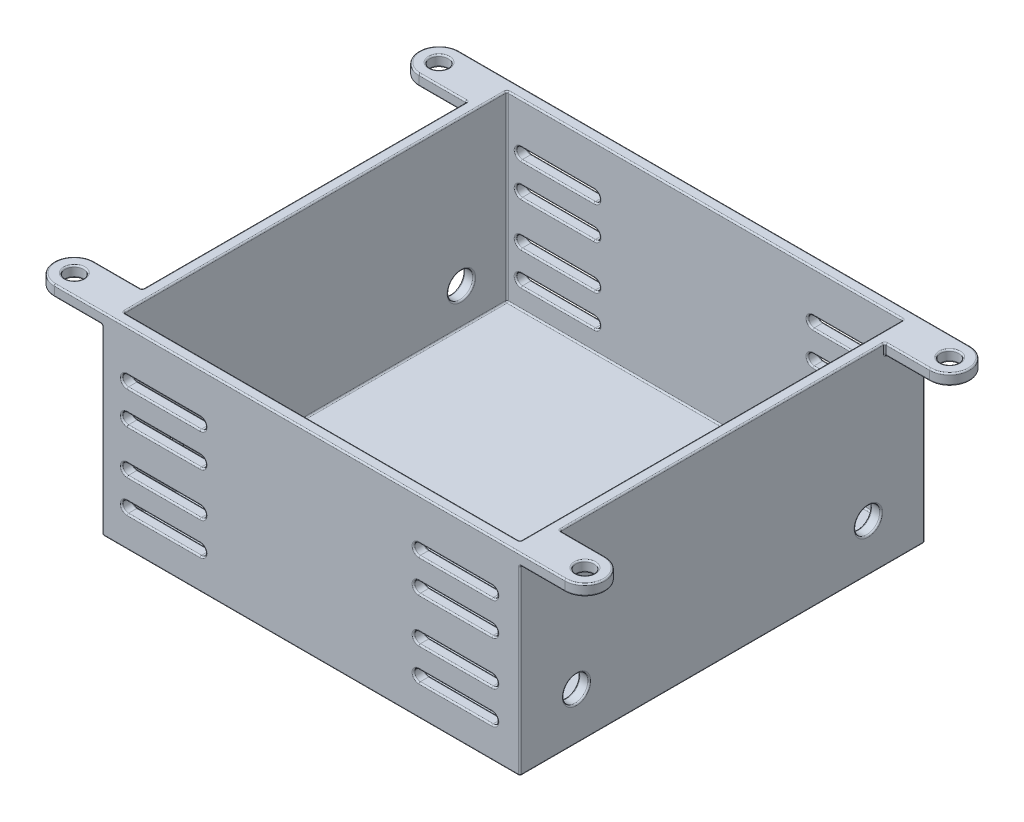
SolidWorks part; units mm, degrees
ref_plane "Front Plane" through (0, 0, 0) normal (0, 0, 1) x (1, 0, 0)
ref_plane "Top Plane" through (0, 0, 0) normal (0, 1, 0) x (1, 0, 0)
ref_plane "Right Plane" through (0, 0, 0) normal (1, 0, 0) x (0, 0, -1)
sketch "Sketch1" plane through (0, 0, 0) normal (0, 1, 0) x (1, 0, 0)
  line L0 (-28.4493, 27.75) -> (-28.4493, -27.75)
  line L1 (-35, -25) -> (35, -25) construction
  line L2 (-35, -25) -> (-35, 25) construction
  line L3 (-35, 25) -> (35, 25) construction
  line L4 (35, -25) -> (35, 25) construction
  line L5 (-35, -25) -> (35, 25) construction
  line L6 (-35, 25) -> (35, -25) construction
  line L7 (-35, -27.75) -> (35, -27.75) construction
  line L8 (-35, 27.75) -> (35, 27.75) construction
  line L9 (-28.4493, -27.75) -> (28.8446, -27.75)
  line L10 (28.8446, -27.75) -> (28.8446, 27.75)
  line L11 (28.8446, 27.75) -> (-28.4493, 27.75)
  line L12 (-35, 22.25) -> (-28.4493, 22.25)
  line L13 (-35, -22.25) -> (-28.4493, -22.25)
  line L14 (35, 22.25) -> (28.8446, 22.25)
  line L15 (28.8446, -27.75) -> (35, -27.75)
  line L16 (-35, -27.75) -> (-28.4493, -27.75)
  line L17 (35, -22.25) -> (28.8446, -22.25)
  line L18 (-28.4493, 27.75) -> (-35, 27.75)
  line L19 (28.8446, 27.75) -> (35, 27.75)
  circle A0 centre (-35, 25) radius 1.25
  circle A1 centre (35, 25) radius 1.25
  circle A2 centre (-35, -25) radius 1.25
  circle A3 centre (35, -25) radius 1.25
  circle A4 centre (35, -25) radius 2.75
  circle A5 centre (35, 25) radius 2.75
  circle A6 centre (-35, 25) radius 2.75
  circle A7 centre (-35, -25) radius 2.75
  point P0 (0, 0)
  dimension "D3" = 2.5
  dimension "D1" = 70
  dimension "D2" = 50
  dimension "D4" = 1.5
  dimension "D5" = 1.5
  dimension "D6" = 1.5
  dimension "D7" = 1.5
sketch "Sketch2" plane through (0, 0, 0) normal (0, 1, 0) x (1, 0, 0)
  line L0 (-28.4493, -27.75) -> (28.8446, -27.75) construction
  line L1 (28.8446, -27.75) -> (28.8446, 27.75) construction
  line L2 (28.8446, 27.75) -> (-28.4493, 27.75) construction
  line L3 (-28.4493, 27.75) -> (-28.4493, -27.75) construction
  line L4 (28.8446, -27.75) -> (28.8446, 27.75)
  line L5 (-28.4493, -27.75) -> (28.8446, -27.75)
  line L6 (-28.4493, 27.75) -> (-28.4493, -27.75)
  line L7 (28.8446, 27.75) -> (-28.4493, 27.75)
  line L8 (27.3446, 26.25) -> (-26.9493, 26.25)
  line L9 (-26.9493, 26.25) -> (-26.9493, -26.25)
  line L10 (-26.9493, -26.25) -> (27.3446, -26.25)
  line L11 (27.3446, -26.25) -> (27.3446, 26.25)
  dimension "D1" = 1.5
extrude "Boss-Extrude1" add sketch "Sketch2" against normal blind 25
sketch "Sketch3" plane through (0, -25, 0) normal (0, -1, 0) x (1, 0, 0)
  line L0 (-28.4493, -27.75) -> (-28.4493, 27.75) construction
  line L1 (28.8446, -27.75) -> (-28.4493, -27.75) construction
  line L2 (28.8446, 27.75) -> (28.8446, -27.75) construction
  line L3 (-28.4493, 27.75) -> (28.8446, 27.75) construction
  line L4 (-28.4493, -27.75) -> (-28.4493, 27.75)
  line L5 (28.8446, -27.75) -> (-28.4493, -27.75)
  line L6 (28.8446, 27.75) -> (28.8446, -27.75)
  line L7 (-28.4493, 27.75) -> (28.8446, 27.75)
extrude "Boss-Extrude2" add sketch "Sketch3" along normal blind 1.5
sketch "Sketch4" plane through (0, 0, 0) normal (0, 1, 0) x (1, 0, 0)
  line L0 (-28.4493, 27.75) -> (-35, 27.75) construction
  line L1 (-35, 22.25) -> (-28.4493, 22.25) construction
  line L2 (-35, -22.25) -> (-28.4493, -22.25) construction
  line L3 (-35, -27.75) -> (-28.4493, -27.75) construction
  line L4 (35, -22.25) -> (28.8446, -22.25) construction
  line L5 (28.8446, -27.75) -> (35, -27.75) construction
  line L6 (35, 22.25) -> (28.8446, 22.25) construction
  line L7 (28.8446, 27.75) -> (35, 27.75) construction
  line L8 (-28.4493, 27.75) -> (-35, 27.75)
  line L9 (-35, 22.25) -> (-28.4493, 22.25)
  line L10 (-35, -22.25) -> (-28.4493, -22.25)
  line L11 (-35, -27.75) -> (-28.4493, -27.75)
  line L12 (35, -22.25) -> (28.8446, -22.25)
  line L13 (28.8446, -27.75) -> (35, -27.75)
  line L14 (35, 22.25) -> (28.8446, 22.25)
  line L15 (28.8446, 27.75) -> (35, 27.75)
  circle A0 centre (-35, 25) radius 1.25 construction
  circle A1 centre (-35, 25) radius 2.75 construction
  circle A2 centre (-35, -25) radius 1.25 construction
  circle A3 centre (-35, -25) radius 2.75 construction
  circle A4 centre (35, -25) radius 1.25 construction
  circle A5 centre (35, -25) radius 2.75 construction
  circle A6 centre (35, 25) radius 1.25 construction
  circle A7 centre (35, 25) radius 2.75 construction
  circle A8 centre (-35, 25) radius 1.25
  arc A9 (-35, 27.75) -> (-35, 22.25) centre (-35, 25) ccw
  circle A10 centre (-35, -25) radius 1.25
  arc A11 (-35, -22.25) -> (-35, -27.75) centre (-35, -25) ccw
  circle A12 centre (35, -25) radius 1.25
  arc A13 (35, -27.75) -> (35, -22.25) centre (35, -25) ccw
  circle A14 centre (35, 25) radius 1.25
  arc A15 (35, 22.25) -> (35, 27.75) centre (35, 25) ccw
  line M11 (-28.4493, 27.75) -> (-28.4493, -27.75)
  line M13 (28.8446, -27.75) -> (28.8446, 27.75)
extrude "Boss-Extrude3" add sketch "Sketch4" against normal blind 1.5 contours L10 A11 L11 A10 M11 | L8 A9 L9 A8 M11 | L14 A15 L15 A14 M13 | L13 A13 L12 A12 M13
sketch "Sketch5" plane through (0, 0, 0) normal (0, 0, 1) x (1, 0, 0)
  line L0 (-28.4493, -14) -> (28.8446, -14) construction
  line L1 (-28.4493, -26.5) -> (-28.4493, -1.5) construction
  line L2 (28.8446, -26.5) -> (28.8446, -1.5) construction
  line L3 (0, 0) -> (0, -38.686) construction
  line L4 (-25, -6.5) -> (-15, -6.5) construction
  line L5 (-25, -5.75) -> (-15, -5.75)
  line L6 (-25, -7.25) -> (-15, -7.25)
  line L7 (-25, -11) -> (-15, -11) construction
  line L8 (-25, -10.25) -> (-15, -10.25)
  line L9 (-25, -11.75) -> (-15, -11.75)
  line L10 (-25, -17) -> (-15, -17) construction
  line L11 (-25, -17.75) -> (-15, -17.75)
  line L12 (-25, -16.25) -> (-15, -16.25)
  line L13 (-25, -21.5) -> (-15, -21.5) construction
  line L14 (-25, -22.25) -> (-15, -22.25)
  line L15 (-25, -20.75) -> (-15, -20.75)
  line L16 (-25, -21.5) -> (-15, -21.5) construction
  line L17 (-25, -22.25) -> (-15, -22.25)
  line L18 (-25, -20.75) -> (-15, -20.75)
  line L19 (-25, -17) -> (-15, -17) construction
  line L20 (-25, -17.75) -> (-15, -17.75)
  line L21 (-25, -16.25) -> (-15, -16.25)
  line L22 (-25, -11) -> (-15, -11) construction
  line L23 (-25, -10.25) -> (-15, -10.25)
  line L24 (-25, -11.75) -> (-15, -11.75)
  line L25 (-25, -6.5) -> (-15, -6.5) construction
  line L26 (-25, -5.75) -> (-15, -5.75)
  line L27 (-25, -7.25) -> (-15, -7.25)
  line L28 (28.4493, -14) -> (-28.8446, -14) construction
  line L29 (25, -6.5) -> (15, -6.5) construction
  line L30 (25, -5.75) -> (15, -5.75)
  line L31 (25, -7.25) -> (15, -7.25)
  line L32 (25, -11) -> (15, -11) construction
  line L33 (25, -10.25) -> (15, -10.25)
  line L34 (25, -11.75) -> (15, -11.75)
  line L35 (25, -17) -> (15, -17) construction
  line L36 (25, -17.75) -> (15, -17.75)
  line L37 (25, -16.25) -> (15, -16.25)
  line L38 (25, -21.5) -> (15, -21.5) construction
  line L39 (25, -22.25) -> (15, -22.25)
  line L40 (25, -20.75) -> (15, -20.75)
  line L41 (25, -21.5) -> (15, -21.5) construction
  line L42 (25, -22.25) -> (15, -22.25)
  line L43 (25, -20.75) -> (15, -20.75)
  line L44 (25, -17) -> (15, -17) construction
  line L45 (25, -17.75) -> (15, -17.75)
  line L46 (25, -16.25) -> (15, -16.25)
  line L47 (25, -11) -> (15, -11) construction
  line L48 (25, -10.25) -> (15, -10.25)
  line L49 (25, -11.75) -> (15, -11.75)
  line L50 (25, -6.5) -> (15, -6.5) construction
  line L51 (25, -5.75) -> (15, -5.75)
  line L52 (25, -7.25) -> (15, -7.25)
  arc A0 (-25, -5.75) -> (-25, -7.25) centre (-25, -6.5) ccw
  arc A1 (-15, -7.25) -> (-15, -5.75) centre (-15, -6.5) ccw
  arc A2 (-25, -10.25) -> (-25, -11.75) centre (-25, -11) ccw
  arc A3 (-15, -11.75) -> (-15, -10.25) centre (-15, -11) ccw
  arc A4 (-25, -17.75) -> (-25, -16.25) centre (-25, -17) cw
  arc A5 (-15, -16.25) -> (-15, -17.75) centre (-15, -17) cw
  arc A6 (-25, -22.25) -> (-25, -20.75) centre (-25, -21.5) cw
  arc A7 (-15, -20.75) -> (-15, -22.25) centre (-15, -21.5) cw
  arc A8 (-25, -22.25) -> (-25, -20.75) centre (-25, -21.5) cw
  arc A9 (-15, -20.75) -> (-15, -22.25) centre (-15, -21.5) cw
  arc A10 (-25, -17.75) -> (-25, -16.25) centre (-25, -17) cw
  arc A11 (-15, -16.25) -> (-15, -17.75) centre (-15, -17) cw
  arc A12 (-25, -10.25) -> (-25, -11.75) centre (-25, -11) ccw
  arc A13 (-15, -11.75) -> (-15, -10.25) centre (-15, -11) ccw
  arc A14 (-25, -5.75) -> (-25, -7.25) centre (-25, -6.5) ccw
  arc A15 (-15, -7.25) -> (-15, -5.75) centre (-15, -6.5) ccw
  arc A16 (25, -5.75) -> (25, -7.25) centre (25, -6.5) cw
  arc A17 (15, -7.25) -> (15, -5.75) centre (15, -6.5) cw
  arc A18 (25, -10.25) -> (25, -11.75) centre (25, -11) cw
  arc A19 (15, -11.75) -> (15, -10.25) centre (15, -11) cw
  arc A20 (25, -17.75) -> (25, -16.25) centre (25, -17) ccw
  arc A21 (15, -16.25) -> (15, -17.75) centre (15, -17) ccw
  arc A22 (25, -22.25) -> (25, -20.75) centre (25, -21.5) ccw
  arc A23 (15, -20.75) -> (15, -22.25) centre (15, -21.5) ccw
  arc A24 (25, -22.25) -> (25, -20.75) centre (25, -21.5) ccw
  arc A25 (15, -20.75) -> (15, -22.25) centre (15, -21.5) ccw
  arc A26 (25, -17.75) -> (25, -16.25) centre (25, -17) ccw
  arc A27 (15, -16.25) -> (15, -17.75) centre (15, -17) ccw
  arc A28 (25, -10.25) -> (25, -11.75) centre (25, -11) cw
  arc A29 (15, -11.75) -> (15, -10.25) centre (15, -11) cw
  arc A30 (25, -5.75) -> (25, -7.25) centre (25, -6.5) cw
  arc A31 (15, -7.25) -> (15, -5.75) centre (15, -6.5) cw
  point P11 (-20, -6.5)
  point P16 (-20, -11)
  point P25 (-20, -17)
  point P32 (-20, -21.5)
  point P39 (-20, -21.5)
  point P46 (-20, -17)
  point P53 (-20, -11)
  point P60 (-20, -6.5)
  point P69 (20, -6.5)
  point P76 (20, -11)
  point P83 (20, -17)
  point P90 (20, -21.5)
  point P97 (20, -21.5)
  point P104 (20, -17)
  point P111 (20, -11)
  point P118 (20, -6.5)
  dimension "D1" = 1.5
  dimension "D2" = 10
  dimension "D3" = 1.5
  dimension "D4" = 10
  dimension "D5" = 4.5
  dimension "D6" = 7.5
  dimension "D7" = 20
  dimension "D8" = 20
extrude "Cut-Extrude1" cut sketch "Sketch5" against normal through all and the other way through all contours L5 A1 L6 A0 | L8 A3 L9 A2 | L11 A5 L12 A4 | L14 A7 L15 A6 | L31 A17 L30 A16 | L34 A19 L33 A18 | L36 A21 L37 A20 | L39 A23 L40 A22
sketch "Sketch6" plane through (0, 0, 0) normal (1, 0, 0) x (0, 0, -1)
  line L0 (0, 0) -> (0, -20) construction
  line L1 (0, -20) -> (-20, -20) construction
  circle A0 centre (-20, -20) radius 1.75
  circle A1 centre (20, -20) radius 1.75
  dimension "D1" = 3.5
  dimension "D2" = 20
  dimension "D3" = 20
extrude "Cut-Extrude2" cut sketch "Sketch6" against normal blind 31.5 and the other way blind 31.5
fillet "Fillet1" radius 0.2 196 edges at (-26.9493, -20, -18.25) (27.3446, -20, -21.75) (28.8446, -20, -21.75) (-28.4493, -20, -18.25) (-26.9493, -20, 21.75) (27.3446, -20, 18.25) (28.8446, -20, 18.25) (-28.4493, -20, 21.75) (20, -22.25, -27.75) (14.25, -21.5, -27.75) (20, -20.75, -27.75) (25.75, -21.5, -27.75) (20, -22.25, 27.75) (14.25, -21.5, 27.75) (20, -20.75, 27.75) (25.75, -21.5, 27.75) (20, -17.75, -27.75) (14.25, -17, -27.75) (20, -16.25, -27.75) (25.75, -17, -27.75) (20, -17.75, 27.75) (14.25, -17, 27.75) (20, -16.25, 27.75) (25.75, -17, 27.75) (20, -10.25, -27.75) (14.25, -11, -27.75) (20, -11.75, -27.75) (25.75, -11, -27.75) (20, -10.25, 27.75) (14.25, -11, 27.75) (20, -11.75, 27.75) (25.75, -11, 27.75) (20, -5.75, -27.75) (14.25, -6.5, -27.75) (20, -7.25, -27.75) (25.75, -6.5, -27.75) (20, -5.75, 27.75) (14.25, -6.5, 27.75) (20, -7.25, 27.75) (25.75, -6.5, 27.75) (-20, -22.25, -27.75) (-14.25, -21.5, -27.75) (-20, -20.75, -27.75) (-25.75, -21.5, -27.75) (-20, -22.25, 27.75) (-14.25, -21.5, 27.75) (-20, -20.75, 27.75) (-25.75, -21.5, 27.75) (-20, -17.75, -27.75) (-14.25, -17, -27.75) (-20, -16.25, -27.75) (-25.75, -17, -27.75) (-20, -17.75, 27.75) (-14.25, -17, 27.75) (-20, -16.25, 27.75) (-25.75, -17, 27.75) (-20, -10.25, -27.75) (-14.25, -11, -27.75) (-20, -11.75, -27.75) (-25.75, -11, -27.75) (-20, -10.25, 27.75) (-14.25, -11, 27.75) (-20, -11.75, 27.75) (-25.75, -11, 27.75) (-25.75, -6.5, 27.75) (-20, -7.25, 27.75) (-14.25, -6.5, 27.75) (-20, -5.75, 27.75) (-25.75, -6.5, -27.75) (-20, -7.25, -27.75) (-14.25, -6.5, -27.75) (-20, -5.75, -27.75) (-20, -7.25, 26.25) (-14.25, -6.5, 26.25) (-20, -5.75, 26.25) (-25.75, -6.5, 26.25) (20, -20.75, 26.25) (14.25, -21.5, 26.25) (20, -22.25, 26.25) (25.75, -21.5, 26.25) (20, -16.25, 26.25) (14.25, -17, 26.25) (20, -17.75, 26.25) (25.75, -17, 26.25) (20, -10.25, 26.25) (14.25, -11, 26.25) (20, -11.75, 26.25) (25.75, -11, 26.25) (-20, -11.75, 26.25) (-14.25, -11, 26.25) (-20, -10.25, 26.25) (-25.75, -11, 26.25) (-20, -17.75, 26.25) (-14.25, -17, 26.25) (-20, -16.25, 26.25) (-25.75, -17, 26.25) (-20, -22.25, 26.25) (-14.25, -21.5, 26.25) (-20, -20.75, 26.25) (-25.75, -21.5, 26.25) (20, -5.75, 26.25) (14.25, -6.5, 26.25) (20, -7.25, 26.25) (25.75, -6.5, 26.25) (35, 0, 26.25) (37.75, 0, 25) (37.75, -1.5, 25) (31.9223, 0, 22.25) (31.9223, -1.5, 22.25) (35, -1.5, 26.25) (31.9223, -1.5, 27.75) (28.8446, -1.5, 25) (28.8446, -0.75, 22.25) (35, 0, -23.75) (31.9223, 0, -22.25) (31.9223, -1.5, -22.25) (37.75, 0, -25) (37.75, -1.5, -25) (35, -1.5, -23.75) (31.9223, -1.5, -27.75) (28.8446, -1.5, -25) (28.8446, -0.75, -22.25) (-35, 0, -23.75) (-37.75, 0, -25) (-37.75, -1.5, -25) (-31.7247, 0, -22.25) (-31.7247, -1.5, -22.25) (-35, -1.5, -23.75) (-31.7247, -1.5, -27.75) (-28.4493, -1.5, -25) (-28.4493, -0.75, -22.25) (-35, 0, 26.25) (-31.7247, 0, 22.25) (-31.7247, -1.5, 22.25) (-37.75, 0, 25) (-37.75, -1.5, 25) (-35, -1.5, 26.25) (-31.7247, -1.5, 27.75) (-28.4493, -1.5, 25) (-28.4493, -0.75, 22.25) (0.1976, -26.5, -27.75) (28.8446, -26.5, 0) (0.1976, -26.5, 27.75) (-28.4493, -26.5, 0) (27.3446, 0, 0) (0.1976, 0, -26.25) (-26.9493, 0, 0) (0.1976, 0, 26.25) (27.3446, -25, 0) (0.1976, -25, -26.25) (-26.9493, -25, 0) (0.1976, -25, 26.25) (27.3446, -12.5, -26.25) (-26.9493, -12.5, -26.25) (-26.9493, -12.5, 26.25) (27.3446, -12.5, 26.25) (-28.4493, 0, 0) (0, 0, 27.75) (28.8446, 0, 0) (0, 0, -27.75) (-28.4493, -14, 27.75) (28.8446, -14, -27.75) (-28.4493, -14, -27.75) (-20, -7.25, -26.25) (-14.25, -6.5, -26.25) (-20, -5.75, -26.25) (-25.75, -6.5, -26.25) (20, -20.75, -26.25) (14.25, -21.5, -26.25) (20, -22.25, -26.25) (25.75, -21.5, -26.25) (20, -16.25, -26.25) (14.25, -17, -26.25) (20, -17.75, -26.25) (25.75, -17, -26.25) (20, -10.25, -26.25) (14.25, -11, -26.25) (20, -11.75, -26.25) (25.75, -11, -26.25) (-20, -11.75, -26.25) (-14.25, -11, -26.25) (-20, -10.25, -26.25) (-25.75, -11, -26.25) (-20, -17.75, -26.25) (-14.25, -17, -26.25) (-20, -16.25, -26.25) (-25.75, -17, -26.25) (-20, -22.25, -26.25) (-14.25, -21.5, -26.25) (-20, -20.75, -26.25) (-25.75, -21.5, -26.25) (20, -5.75, -26.25) (14.25, -6.5, -26.25) (20, -7.25, -26.25) (25.75, -6.5, -26.25) (28.8446, -14, 27.75)
